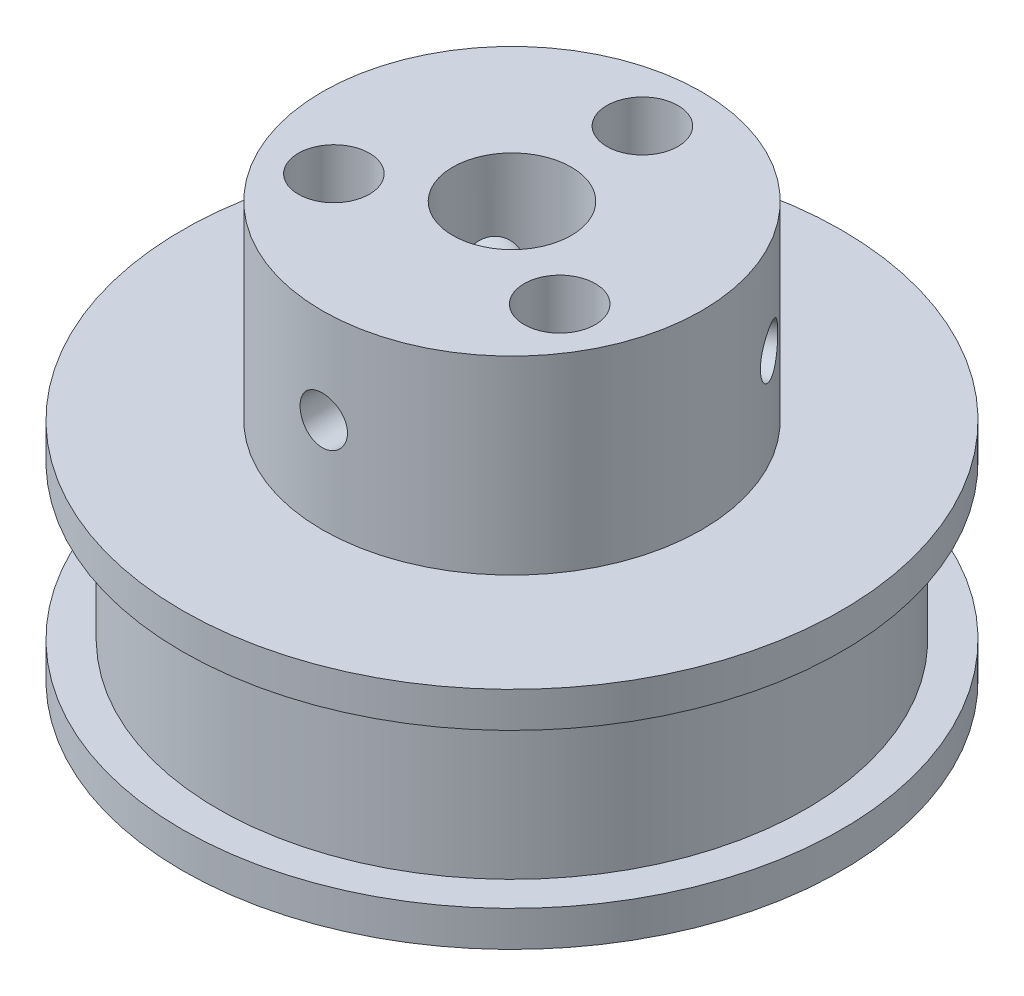
SolidWorks part; units mm, degrees
ref_plane "Face" through (0, 0, 0) normal (0, 0, 1) x (1, 0, 0)
ref_plane "Dessus" through (0, 0, 0) normal (0, 1, 0) x (1, 0, 0)
ref_plane "Droite" through (0, 0, 0) normal (1, 0, 0) x (0, 0, -1)
sketch "Esquisse1" plane through (0, 0, 0) normal (0, 0, 1) x (1, 0, 0)
  line L0 (0, 0) -> (0, 9.7978) construction
  line L1 (2.5, 0) -> (13.9, 0)
  line L2 (13.9, 0) -> (13.9, 1.5)
  line L3 (13.9, 1.5) -> (12.4, 1.5)
  line L4 (12.4, 1.5) -> (12.4, 8)
  line L5 (12.4, 8) -> (13.9, 8)
  line L6 (13.9, 8) -> (13.9, 9.5)
  line L7 (13.9, 9.5) -> (8.85, 9.5)
  line L8 (8.85, 9.5) -> (8.85, 17.5)
  line L9 (8.85, 17.5) -> (2.5, 17.5)
  line L10 (2.5, 17.5) -> (2.5, 0)
  dimension "D1" = 27.8
  dimension "D2" = 6.5
  dimension "D3" = 5
  dimension "D4" = 17.7
  dimension "D5" = 17.5
  dimension "D6" = 1.5
  dimension "D7" = 1.5
  dimension "D8" = 1.5
revolve "Révolution1" add sketch "Esquisse1" angle 360 about L0
sketch "Esquisse2" plane through (0, 17.5, 0) normal (0, 1, 0) x (1, 0, 0)
  circle A0 centre (0, 0) radius 8
  circle A1 centre (0, 0) radius 8.85
  dimension "D1" = 16
extrude "Enlèv. mat.-Extru.1" cut sketch "Esquisse2" against normal blind 8
sketch "Esquisse3" plane through (0, 17.5, 0) normal (0, 1, 0) x (1, 0, 0)
  circle A0 centre (0, 0) radius 5.5 construction
  circle A1 centre (0, 5.5) radius 1.5
  circle A2 centre (4.7631, -2.75) radius 1.5
  circle A3 centre (-4.7631, -2.75) radius 1.5
  point P12 (0, 0)
  dimension "D1" = 11
  dimension "D2" = 3
  dimension "D3" = 3
extrude "Enlèv. mat.-Extru.2" cut sketch "Esquisse3" against normal blind 7
sketch "Esquisse4" plane through (0, 0, 0) normal (0, 0, 1) x (1, 0, 0)
  line L0 (0, 9.5) -> (0, 17.5) construction
  line L1 (13.9, 9.5) -> (-13.9, 9.5) construction
  line L2 (2.5, 17.5) -> (-2.5, 17.5) construction
  circle A0 centre (0, 13.5) radius 1
  dimension "D1" = 2
extrude "Enlèv. mat.-Extru.3" cut sketch "Esquisse4" along normal blind 10
sketch "Esquisse5" plane through (0, 0, 0) normal (1, 0, 0) x (0, 0, -1)
  line L0 (0, -2.3058) -> (0, 20.0015) construction
ref_plane "Plan1" through (0, 0, 0) normal (0.866, 0, 0.5) x (0, 1, 0)
sketch "Esquisse6" plane through (0, 0, 0) normal (0.866, 0, 0.5) x (0, 1, 0)
  line L0 (17.5, 0) -> (9.4998, 0) construction
  line L1 (17.5, -8) -> (17.5, 8) construction
  line L2 (-2.3058, 0) -> (20.0015, 0) construction
  circle A0 centre (13.4999, 0) radius 1
  dimension "D1" = 2
extrude "Enlèv. mat.-Extru.4" cut sketch "Esquisse6" against normal blind 10
ref_plane "Plan2" through (0, 0, 0) normal (0.866, 0, -0.5) x (0, 1, 0)
sketch "Esquisse7" plane through (0, 0, 0) normal (0.866, 0, -0.5) x (0, 1, 0)
  line L0 (17.5, 0) -> (9.5, 0) construction
  line L1 (17.5, -8) -> (17.5, 8) construction
  line L2 (9.5, -8) -> (9.5, 8) construction
  circle A0 centre (13.5, 0) radius 1
  dimension "D1" = 2
extrude "Enlèv. mat.-Extru.5" cut sketch "Esquisse7" along normal blind 10
